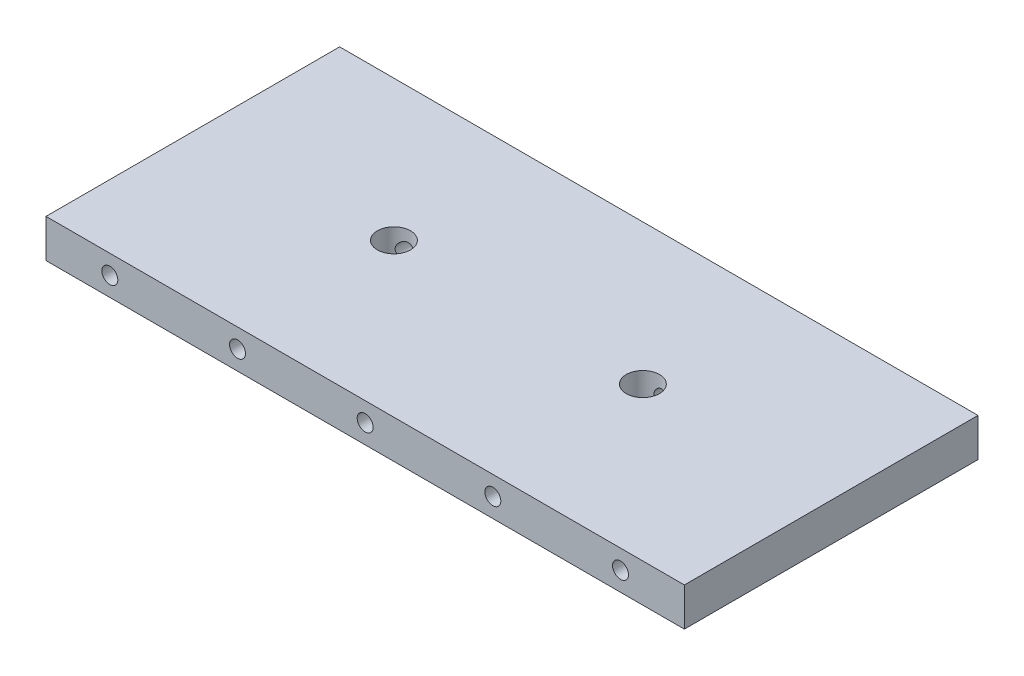
SolidWorks part; units mm, degrees
material "6061-T6 (SS)"
ref_plane "Front Plane" through (0, 0, 0) normal (0, 0, 1) x (1, 0, 0)
ref_plane "Top Plane" through (0, 0, 0) normal (0, 1, 0) x (1, 0, 0)
ref_plane "Right Plane" through (0, 0, 0) normal (1, 0, 0) x (0, 0, -1)
sketch "Sketch1" plane through (0, 0, 0) normal (0, 1, 0) x (1, 0, 0)
  line L1 (0, 0) -> (100, 0)
  line L2 (0, 0) -> (0, 46)
  line L3 (0, 46) -> (100, 46)
  line L4 (100, 0) -> (100, 46)
  dimension "D1" = 100
  dimension "D2" = 46
extrude "Boss-Extrude1" add sketch "Sketch1" along normal blind 6
sketch "Sketch5" plane through (0, 0, -46) normal (0, 0, -1) x (-1, 0, 0)
  line L1 (-100, 0) -> (0, 0) construction
  line L3 (-50, 3) -> (-50, 6) construction
  line L4 (-100, 6) -> (0, 6) construction
  point P0 (-90, 3)
  point P12 (-70, 3)
  point P13 (-50, 3)
  point P14 (-30, 3)
  point P15 (-10, 3)
  dimension "D1" = 3
  dimension "D2" = 5
  dimension "D3" = 20
hole_wizard "Tap Drill for M3 Tap1" positions "Sketch5" profile "Sketch7" hole size "M3" standard "DIN" end condition through all
sketch "Sketch7" plane through (90, 3, -46) normal (1, 0, 0) x (0, 1, 0)
  line L0 (0, 0) -> (0, 46)
  line L1 (0, 46) -> (1.25, 46)
  line L2 (1.25, 46) -> (1.25, 0)
  line L5 (1.25, 0) -> (0, 0)
  line L11 (0, -6.35) -> (0, 107.95) construction
  dimension "Thru Hole Dia." = 2.5
  dimension "Thru Hole Depth" = 46
sketch "Sketch10" plane through (0, 6, 0) normal (0, 1, 0) x (1, 0, 0)
  point P0 (30.5, 24)
  point P3 (69.5, 24)
hole_wizard "Tap Drill for M5 Helicoil1" positions "Sketch10" profile "Sketch11" hole size "M5x0.8" standard "DIN" end condition through all
sketch "Sketch11" plane through (30.5, 6, -24) normal (1, 0, 0) x (0, 0, 1)
  line L0 (0, 0) -> (0, 6)
  line L1 (0, 6) -> (2.6, 6)
  line L2 (2.6, 6) -> (2.6, 0)
  line L5 (2.6, 0) -> (0, 0)
  line L11 (0, -6.35) -> (0, 107.95) construction
  dimension "Thru Hole Dia." = 5.2
  dimension "Thru Hole Depth" = 6
